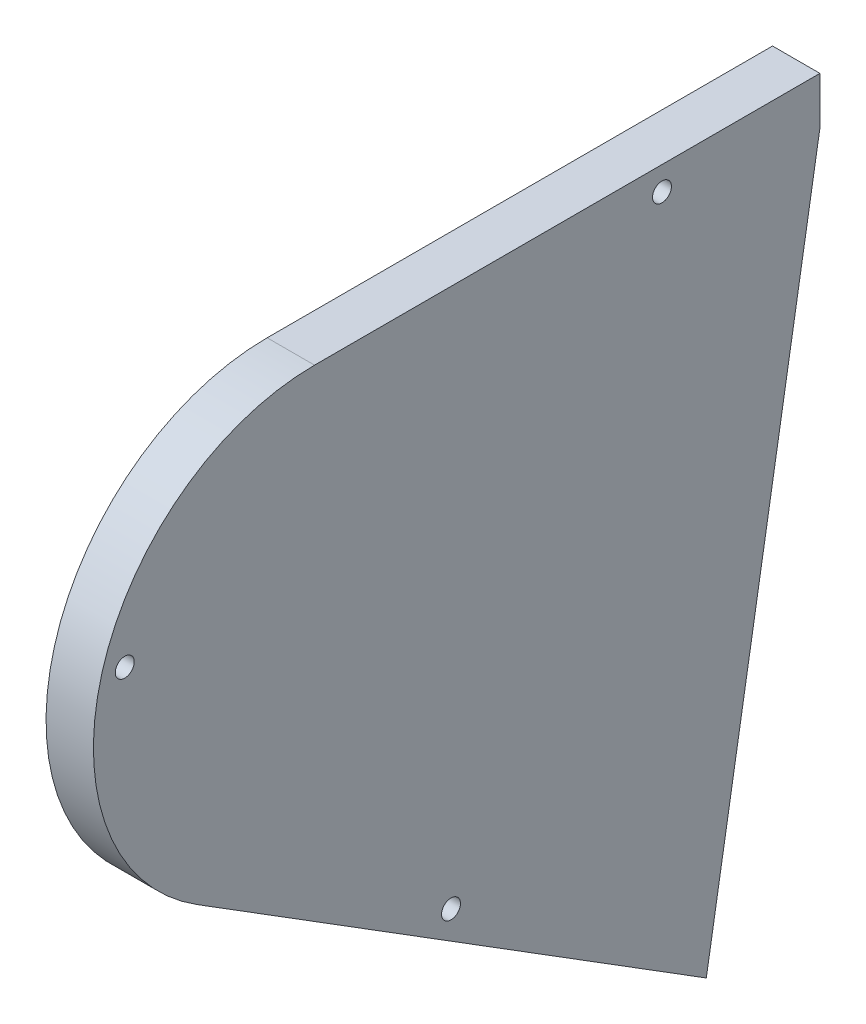
SolidWorks part; units mm, degrees
ref_plane "前视基准面" through (0, 0, 0) normal (0, 0, 1) x (1, 0, 0)
ref_plane "上视基准面" through (0, 0, 0) normal (0, 1, 0) x (1, 0, 0)
ref_plane "右视基准面" through (0, 0, 0) normal (1, 0, 0) x (0, 0, -1)
other "Configuration Table"
sketch "草图2" plane through (0, 0, 0) normal (0, 1, 0) x (1, 0, 0)
  line L15 (-1.5, 0) -> (1.5, 0)
  line L16 (-1.5, 0) -> (-1.5, -32)
  line L17 (-1.5, -32) -> (1.5, -32)
  line L18 (1.5, 0) -> (1.5, -32)
  dimension "D1" = 3
  dimension "D2" = 32
extrude "凸台-拉伸1" add sketch "草图2" along normal blind 3
sketch "草图3" plane through (1.5, 0, 0) normal (1, 0, 0) x (0, 0, -1)
  line L1 (-37.8291, -20.3285) -> (-5.6033, -40.4655)
  line L2 (-37.8291, -20.3285) -> (-39.4189, -22.8727)
  line L3 (-39.4189, -22.8727) -> (-7.193, -43.0096)
  line L4 (-5.6033, -40.4655) -> (-7.193, -43.0096)
  line L5 (-37.8291, -20.3285) -> (-32, 0)
  line L6 (-32, 0) -> (-23.3397, 0)
  circle A0 centre (-32, -11) radius 14
  circle A1 centre (-32, -11) radius 11
  line M6 (-32, 3) -> (-32, 0)
  dimension "D1" = 28
  dimension "D2" = 3
  dimension "D3" = 32
  dimension "D4" = 38
extrude "凸台-拉伸2" add sketch "草图3" against normal up to surface (3 mm away) contours A1 A0 L2 M6
sketch "草图4" plane through (1.5, 0, 0) normal (1, 0, 0) x (0, 0, -1)
  line L0 (0, 0) -> (-7.193, -43.0096)
  line L6 (-32, 0) -> (0, 0)
  line L7 (0, 0) -> (0, 3)
  line L8 (0, 3) -> (-32, 3)
  line L9 (-39.4189, -22.8727) -> (-7.193, -43.0096)
  line L10 (-7.193, -43.0096) -> (-5.6033, -40.4655)
  line L11 (-5.6033, -40.4655) -> (-37.8291, -20.3285)
  line L12 (-32, 0) -> (0, 0)
  line L13 (0, 0) -> (0, 3)
  line L14 (0, 3) -> (-32, 3)
  line L15 (-39.4189, -22.8727) -> (-7.193, -43.0096)
  line L16 (-7.193, -43.0096) -> (-5.6033, -40.4655)
  line L17 (-5.6033, -40.4655) -> (-37.8291, -20.3285)
  arc A2 (-32, 3) -> (-39.4189, -22.8727) centre (-32, -11) ccw
  arc A3 (-32, 0) -> (-37.8291, -20.3285) centre (-32, -11) ccw
  arc A4 (-32, 3) -> (-39.4189, -22.8727) centre (-32, -11) ccw
  arc A5 (-32, 0) -> (-37.8291, -20.3285) centre (-32, -11) ccw
  dimension "D1" = 0
extrude "凸台-拉伸3" add sketch "草图4" against normal up to surface (3 mm away) up to face at (-1.5, -14.4606, 21.4315)
sketch "草图5" plane through (1.5, 0, 0) normal (1, 0, 0) x (0, 0, -1)
  line L0 (-6.6574, -39.8068) -> (-7.193, -43.0096)
  line L1 (-6.6574, -39.8068) -> (-5.6033, -40.4655) construction
  line L2 (-5.6033, -40.4655) -> (-7.193, -43.0096) construction
  line L3 (-39.4189, -22.8727) -> (-7.193, -43.0096) construction
  line L4 (0, 0) -> (-6.6574, -39.8068) construction
  point P8 (-6.6574, -39.8068)
  line M8 (-7.193, -43.0096) -> (-5.6033, -40.4655)
  line M9 (-5.6033, -40.4655) -> (-6.6574, -39.8068)
extrude "切除-拉伸1" cut sketch "草图5" against normal blind 3 and the other way through all contours L0 M9 M8
sketch "草图6" plane through (1.5, 0, 0) normal (1, 0, 0) x (0, 0, -1)
  circle A0 centre (-10, 1.5) radius 1
  circle A1 centre (-10, 1.5) radius 0.6
  circle A2 centre (-44.0158, -7.5545) radius 1
  circle A3 centre (-44.0158, -7.5545) radius 0.6
  circle A4 centre (-23.3591, -31.1391) radius 1
  circle A5 centre (-23.3591, -31.1391) radius 0.6
  point P6 (0, 0)
  point P9 (-23.0726, -31.1391)
  dimension "D1" = 1.2
  dimension "D2" = 2
extrude "切除-拉伸2" cut sketch "草图6" against normal through all contours A3 | A5 | A1
